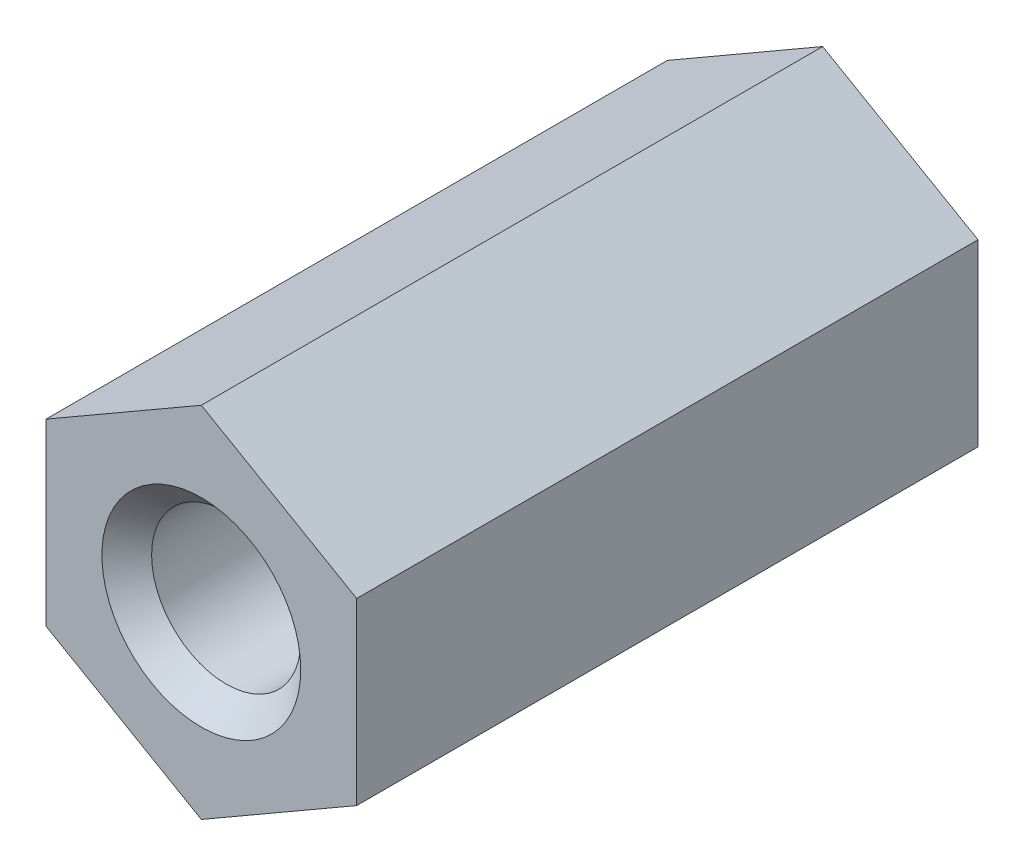
SolidWorks part; units mm, degrees
ref_plane "Спереди" through (0, 0, 0) normal (0, 0, 1) x (1, 0, 0)
ref_plane "Сверху" through (0, 0, 0) normal (0, 1, 0) x (1, 0, 0)
ref_plane "Справа" through (0, 0, 0) normal (1, 0, 0) x (0, 0, -1)
sketch "Эскиз1" plane through (0, 0, 0) normal (0, 0, 1) x (1, 0, 0)
  line L1 (0, 2.8868) -> (-2.5, 1.4434)
  line L2 (-2.5, 1.4434) -> (-2.5, -1.4434)
  line L3 (-2.5, -1.4434) -> (0, -2.8868)
  line L4 (0, -2.8868) -> (2.5, -1.4434)
  line L5 (2.5, -1.4434) -> (2.5, 1.4434)
  line L6 (2.5, 1.4434) -> (0, 2.8868)
  circle A0 centre (0, 0) radius 2.5 construction
  circle A1 centre (0, 0) radius 1.2
  dimension "D1" = 2.4
  dimension "D2" = 5
extrude "Вытянуть1" add sketch "Эскиз1" along normal blind 10
cosmetic thread "Условное изображение резьбы1" parameters "D1"=10, "D2"=3
chamfer "Фаска1" distance 0.4 angle 45 2 edges at (1.2, 0, 10) (1.2, 0, 0)
